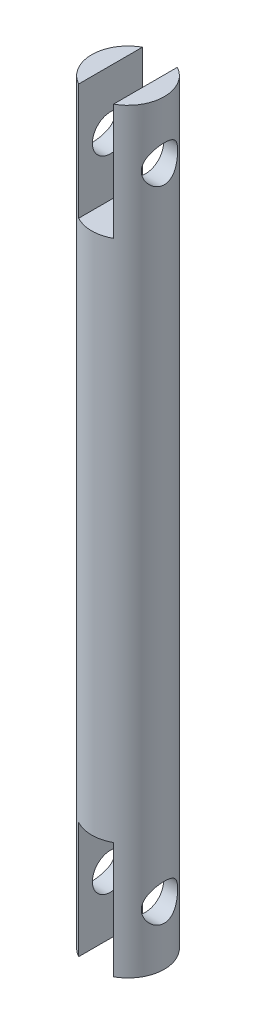
SolidWorks part; units mm, degrees
ref_plane "Front Plane" through (0, 0, 0) normal (1, 0, 0) x (0, 1, 0)
ref_plane "Top Plane" through (0, 0, 0) normal (0, 0, 1) x (0, 1, 0)
ref_plane "Right Plane" through (0, 0, 0) normal (0, 1, 0) x (-1, 0, 0)
sketch "Sketch2" plane through (0, 0, 0) normal (0, 1, 0) x (-1, 0, 0)
  circle A0 centre (0, 0) radius 2.5
  dimension "D1" = 5
extrude "Boss-Extrude1" add sketch "Sketch2" along normal blind 52 contours A0
sketch "Sketch3" plane through (0, 0, 0) normal (0, -1, 0) x (1, 0, 0)
  line L1 (-1.2, -2.5) -> (1.2, -2.5)
  line L2 (-1.2, -2.5) -> (-1.2, 2.5)
  line L3 (-1.2, 2.5) -> (1.2, 2.5)
  line L4 (1.2, -2.5) -> (1.2, 2.5)
  line L5 (-1.2, -2.5) -> (1.2, 2.5) construction
  line L6 (-1.2, 2.5) -> (1.2, -2.5) construction
  circle A0 centre (0, 0) radius 2.5 construction
  point P0 (0, 0)
  dimension "D1" = 2.4
extrude "Cut-Extrude1" cut sketch "Sketch3" against normal blind 8 contours L2 L3 L4 L1
sketch "Sketch4" plane through (0, 0, 0) normal (1, 0, 0) x (0, 1, 0)
  line L0 (0, 0) -> (52, 0) construction
  line L1 (52, -2.5) -> (52, 2.5) construction
  line L2 (0, 2.1932) -> (0, -2.1932) construction
  circle A0 centre (4, 0) radius 1.25
  circle A1 centre (48, 0) radius 1.25
  point P9 (49.0665, 0)
  point P10 (8.3413, 0)
  point P11 (0, 0)
  dimension "D2" = 2.5
  dimension "D1" = 44
  dimension "D3" = 4
extrude "Cut-Extrude2" cut sketch "Sketch4" against normal through all and the other way through all
sketch "Sketch5" plane through (0, 52, 0) normal (0, 1, 0) x (-1, 0, 0)
  line L1 (-1.2, -2.5) -> (1.2, -2.5)
  line L2 (-1.2, -2.5) -> (-1.2, 2.5)
  line L3 (-1.2, 2.5) -> (1.2, 2.5)
  line L4 (1.2, -2.5) -> (1.2, 2.5)
  line L5 (-1.2, -2.5) -> (1.2, 2.5) construction
  line L6 (-1.2, 2.5) -> (1.2, -2.5) construction
  circle A0 centre (0, 0) radius 2.5 construction
  point P0 (0, 0)
  dimension "D1" = 2.4
extrude "Cut-Extrude3" cut sketch "Sketch5" against normal blind 8
